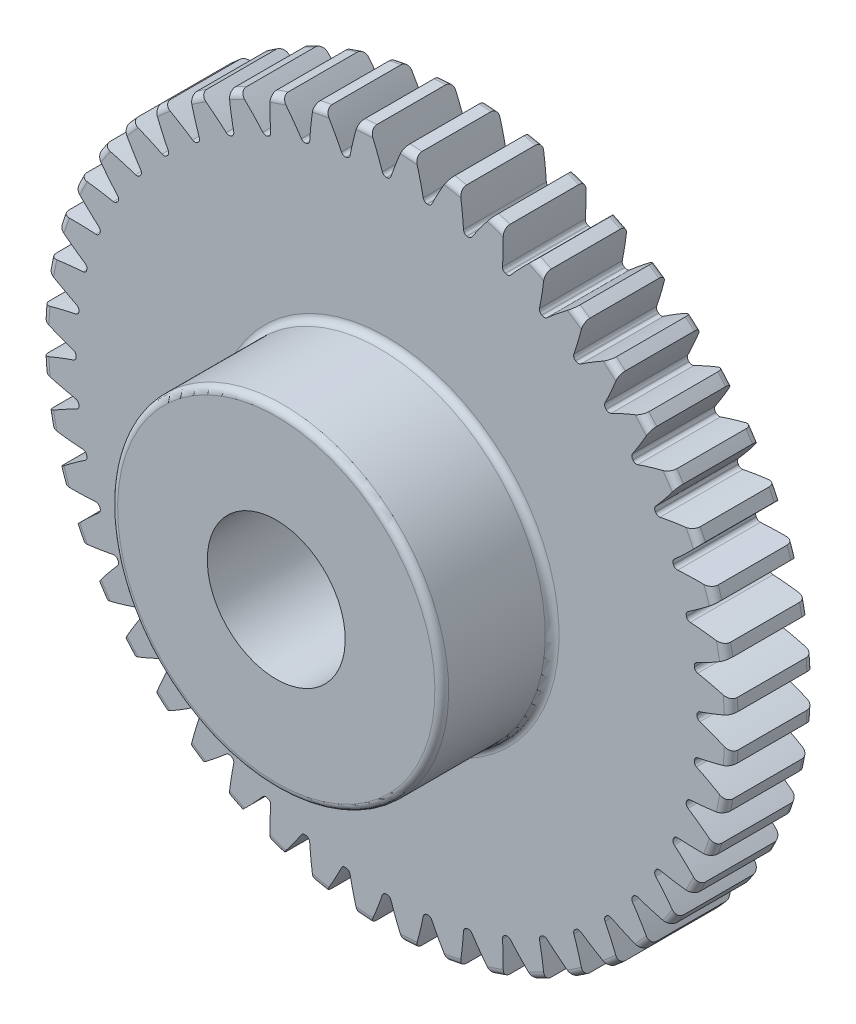
SolidWorks part; units mm, degrees
ref_plane "Front Plane" through (0, 0, 0) normal (0, 0, 1) x (1, 0, 0)
ref_plane "Top Plane" through (0, 0, 0) normal (0, 1, 0) x (1, 0, 0)
ref_plane "Right Plane" through (0, 0, 0) normal (1, 0, 0) x (0, 0, -1)
sketch "Sketch1" plane through (0, 0, 0) normal (0, 0, 1) x (1, 0, 0)
  line L0 (-609.6, 0) -> (609.6, 0) construction
  circle A0 centre (0, 0) radius 12.5 construction
  circle A1 centre (0, 0) radius 12 construction
  circle A2 centre (0, 0) radius 11.25 construction
  circle A3 centre (0, 0) radius 6 construction
  circle A4 centre (0, 0) radius 2.5 construction
  dimension "D2" = 0.5
  dimension "D3" = 1.25
  dimension "D1" = 1.25
sketch "Sketch2" plane through (0, 0, 0) normal (1, 0, 0) x (0, 0, -1)
  line L0 (0, 0) -> (-3, 0) construction
  line L1 (-3, 0) -> (-7, 0) construction
  dimension "Overall Width" = 7
  dimension "Face Width" = 3
sketch "Sketch4" plane through (0, 0, 0) normal (1, 0, 0) x (0, 0, -1)
  line L0 (-7, 2.5) -> (-7, 6)
  line L1 (-7, 6) -> (-3, 6)
  line L2 (-3, 6) -> (-3, 12.5)
  line L3 (-3, 12.5) -> (0, 12.5)
  line L4 (0, 12.5) -> (0, 2.5)
  line L5 (-3, 6) -> (-3, 0) construction
  line L6 (0, 12.5) -> (0, -12.5) construction
  line L7 (-3, 6) -> (0, 6) construction
  line L12 (-7, 2.5) -> (0, 2.5)
revolve "Revolve1" add sketch "Sketch4" angle 360 about L1
fillet "Fillet2" radius 0.25 4 edges at (0, 6, 7) (0, 6, 3) (0, 12.5, 3) (0, 12.5, 0)
sketch "Sketch7" plane through (0, 0, 3) normal (0, 0, 1) x (1, 0, 0)
  line L0 (0, 0) -> (0, 12.5) construction
  line L1 (0.3926, 11.9936) -> (0.5904, 12.4861) construction
  line L3 (0.8175, 12.4732) -> (0.7848, 11.9743) construction
  line L4 (0.7848, 11.9743) -> (0.7358, 11.2259) construction
  line L5 (0, 0) -> (0.7358, 11.2259) construction
  line L6 (0.3926, 11.9936) -> (0, 0) construction
  line L7 (0.3926, 11.9936) -> (0.409, 12.4933) construction
  line L8 (0.3926, 11.9936) -> (0, 0) construction
  circle A0 centre (0, 0) radius 12.5 construction
  arc A1 (-0.0137, 11.25) -> (0.0137, 11.25) centre (0, 0) cw
  circle A2 centre (0, 0) radius 11.25 construction
  arc A3 (-0.3926, 11.9936) -> (0.3926, 11.9936) centre (0, 0) cw construction
  circle A4 centre (0, 0) radius 12 construction
  arc A5 (1.0319, 12.4573) -> (0.603, 12.4854) centre (0, 0) ccw construction
  arc A6 (0.3926, 11.9936) -> (1.1762, 11.9422) centre (0, 0) cw construction
  arc A7 (-0.603, 12.4854) -> (0.603, 12.4854) centre (0, 0) cw
  arc A8 (0.1561, 11.3521) -> (0.603, 12.4854) centre (11.5286, 7.5226) cw
  arc A9 (-0.1561, 11.3521) -> (-0.603, 12.4854) centre (-11.5286, 7.5226) ccw
  arc A10 (-0.0137, 11.25) -> (-0.1561, 11.3521) centre (-0.0139, 11.4) cw
  arc A11 (0.0137, 11.25) -> (0.1561, 11.3521) centre (0.0139, 11.4) ccw
  point P26 (-0.122, 11.2493)
  point P29 (0.122, 11.2493)
  dimension "D4" = 0.15
  dimension "D5" = 12
  dimension "D3" = 20
  dimension "D1" = 1.5708
  dimension "D2" = 0.7854
extrude "Cut-Extrude2" cut sketch "Sketch7" against normal through all
pattern_circular "CirPattern1" count 48 over 360 about axis through (0, 0, 0) along (0, 0, 1) of "Cut-Extrude2"
equation "\"D1@Sketch1\"=2.5*(\"Pitch Dia.@Sketch1\"/\"Number of Teeth@Sketch1\")"
equation "\"D1@CirPattern1\"=\"Number of Teeth@Sketch1\""
equation "\"D1@Fillet2\"=\"OD@Sketch1\"*.01"
equation "\"D1@Sketch7\"=3.14159*(\"Pitch Dia.@Sketch1\"/\"Number of Teeth@Sketch1\")"
equation "\"D2@Sketch7\"=\"D1@Sketch7\"/2"
equation "\"D4@Sketch7\"=\"D1@Sketch7\"*.0955"
equation "\"D5@Sketch7\"=\"Pitch Dia.@Sketch1\"/2"
